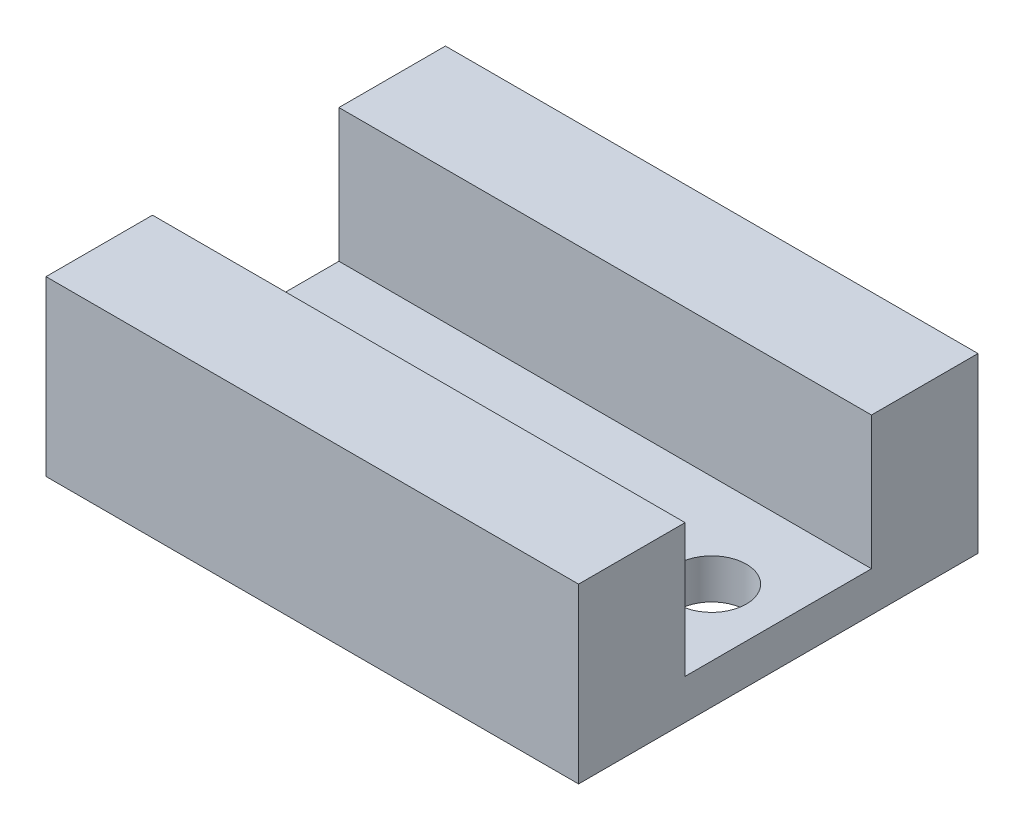
SolidWorks part; units mm, degrees
ref_plane "前视基准面" through (0, 0, 0) normal (0, 0, 1) x (1, 0, 0)
ref_plane "上视基准面" through (0, 0, 0) normal (0, 1, 0) x (1, 0, 0)
ref_plane "右视基准面" through (0, 0, 0) normal (1, 0, 0) x (0, 0, -1)
sketch "草图1" plane through (0, 0, 0) normal (0, 1, 0) x (1, 0, 0)
  line L0 (0, 0) -> (7.5, 0) construction
  line L1 (-10, 7.5) -> (10, 7.5)
  line L2 (-10, 7.5) -> (-10, -7.5)
  line L3 (-10, -7.5) -> (10, -7.5)
  line L4 (10, 7.5) -> (10, -7.5)
  line L5 (-10, 7.5) -> (10, -7.5) construction
  line L6 (-10, -7.5) -> (10, 7.5) construction
  line L7 (7.5, 0) -> (-7.5, 0) construction
  circle A0 centre (7.5, 0) radius 1.3
  circle A1 centre (-7.5, 0) radius 1.3
  point P0 (0, 0)
  dimension "D5" = 2.6
  dimension "D6" = 2.6
  dimension "D1" = 15
  dimension "D2" = 20
  dimension "D3" = 15
  dimension "D4" = 7.5
extrude "凸台-拉伸1" add sketch "草图1" along normal blind 1.5
ref_plane "基准面1" through (0, 1.5, 0) normal (0, 1, 0) x (1, 0, 0)
sketch "草图2" plane through (0, 1.5, 0) normal (0, 1, 0) x (1, 0, 0)
  line L0 (10, -7.5) -> (10, 7.5) construction
  line L1 (-10, 7.5) -> (10, 7.5)
  line L2 (-10, 7.5) -> (-10, 3.5)
  line L3 (-10, 3.5) -> (10, 3.5)
  line L4 (10, 7.5) -> (10, 3.5)
  line L6 (-10, -7.5) -> (10, -7.5)
  line L7 (-10, -7.5) -> (-10, -3.5)
  line L8 (-10, -3.5) -> (10, -3.5)
  line L9 (10, -7.5) -> (10, -3.5)
  dimension "D1" = 4
  dimension "D2" = 4
extrude "凸台-拉伸2" add sketch "草图2" along normal blind 5
